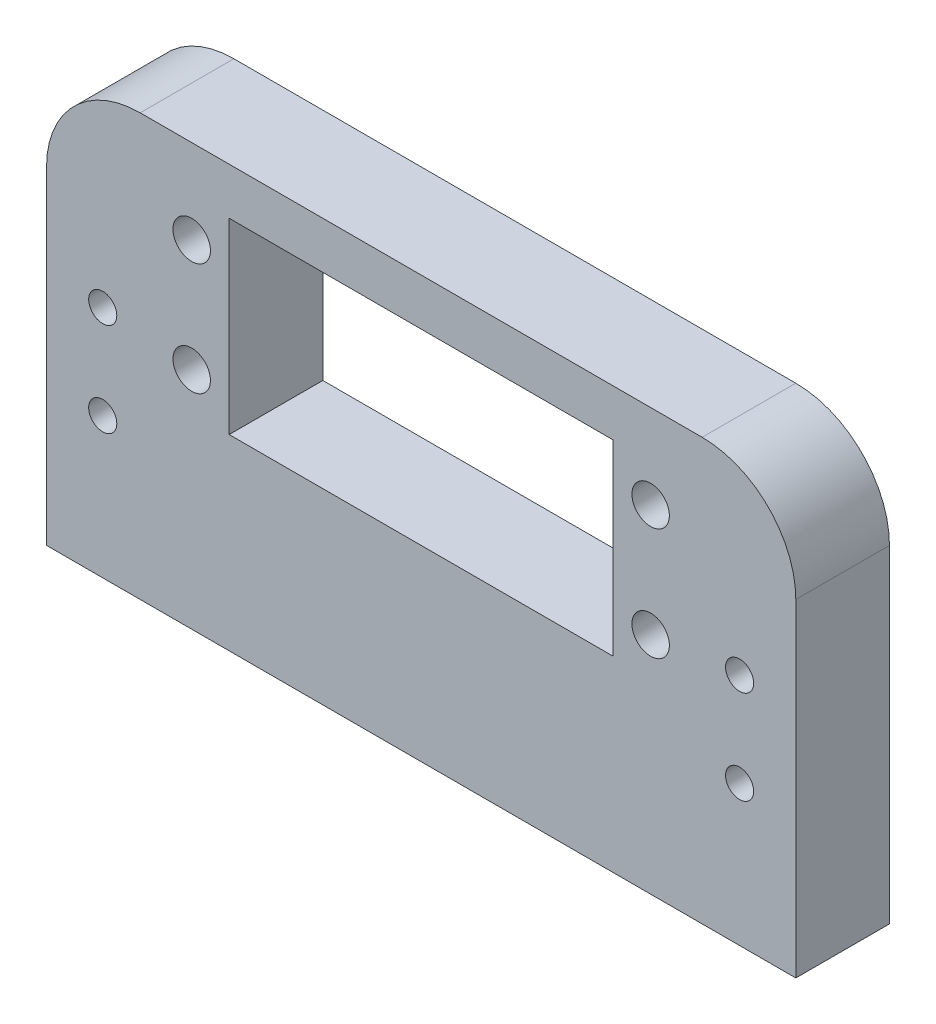
SolidWorks part; units mm, degrees
ref_plane "Front Plane" through (0, 0, 0) normal (0, 0, 1) x (1, 0, 0)
ref_plane "Top Plane" through (0, 0, 0) normal (0, 1, 0) x (1, 0, 0)
ref_plane "Right Plane" through (0, 0, 0) normal (1, 0, 0) x (0, 0, -1)
sketch "Sketch1" plane through (0, 0, 0) normal (0, 0, 1) x (1, 0, 0)
  line L0 (-6.0365, 24.5708) -> (-14.4685, 24.5708) construction
  line L1 (-15.5365, 29.5708) -> (44.4635, 29.5708)
  line L2 (-25.5365, 19.5708) -> (-25.5365, -15.4292)
  line L3 (-25.5365, -15.4292) -> (54.4635, -15.4292)
  line L4 (54.4635, 19.5708) -> (54.4635, -15.4292)
  line L5 (-6.0365, 24.5708) -> (34.9635, 24.5708)
  line L6 (-6.0365, 24.5708) -> (-6.0365, 4.5708)
  line L7 (-6.0365, 4.5708) -> (34.9635, 4.5708)
  line L8 (34.9635, 24.5708) -> (34.9635, 4.5708)
  line L9 (-6.0365, 14.5708) -> (34.9635, 14.5708) construction
  line L10 (14.4635, 29.5708) -> (14.4635, -15.4292) construction
  circle A0 centre (-10.0365, 20.5708) radius 2
  circle A1 centre (38.9635, 8.5708) radius 2
  circle A2 centre (-10.0365, 8.5708) radius 2
  circle A3 centre (38.9635, 20.5708) radius 2
  circle A4 centre (-19.5365, -0.4292) radius 1.5
  circle A5 centre (-19.5365, 9.5708) radius 1.5
  circle A6 centre (48.4635, 9.5708) radius 1.5
  circle A7 centre (48.4635, -0.4292) radius 1.5
  arc A8 (54.4635, 19.5708) -> (44.4635, 29.5708) centre (44.4635, 19.5708) ccw
  arc A9 (-15.5365, 29.5708) -> (-25.5365, 19.5708) centre (-15.5365, 19.5708) ccw
  dimension "D7" = 4
  dimension "D10" = 3
  dimension "D11" = 3
  dimension "D16" = 10
  dimension "D2" = 45
  dimension "D3" = 41
  dimension "D4" = 20
  dimension "D5" = 5
  dimension "D6" = 19.5
  dimension "D8" = 4
  dimension "D9" = 4
  dimension "D12" = 15
  dimension "D13" = 10
  dimension "D14" = 6
  dimension "D15" = 80
extrude "Boss-Extrude1" add sketch "Sketch1" along normal blind 10
